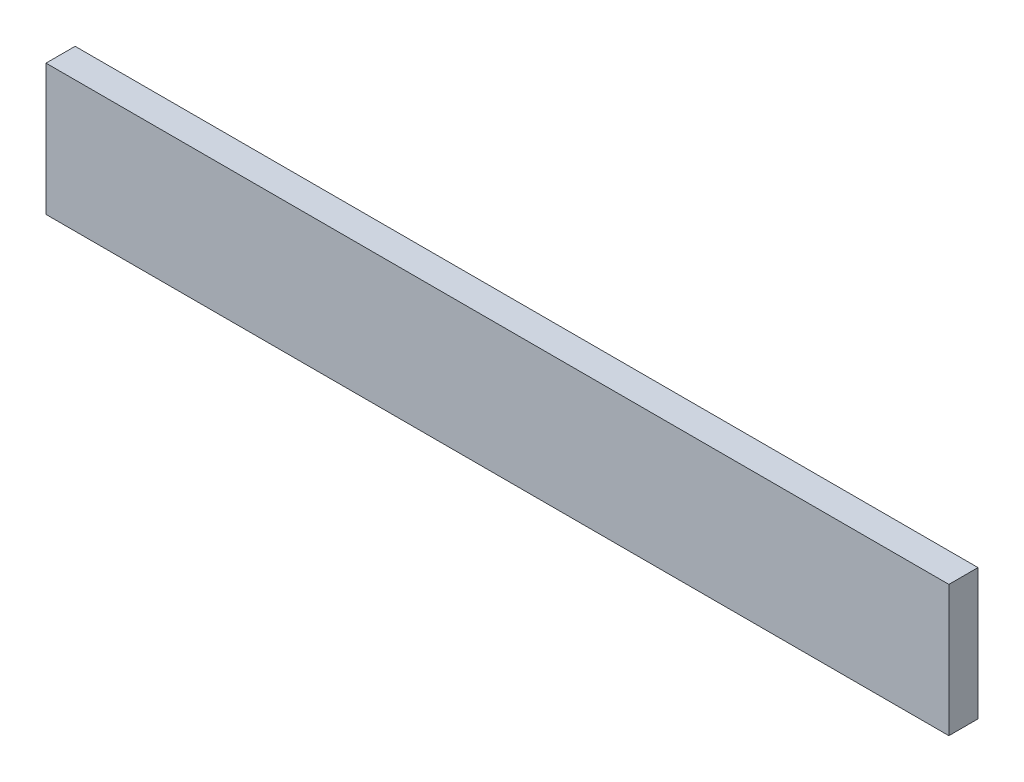
SolidWorks part; units mm, degrees
ref_plane "Alzado" through (0, 0, 0) normal (0, 0, 1) x (1, 0, 0)
ref_plane "Planta" through (0, 0, 0) normal (0, 1, 0) x (1, 0, 0)
ref_plane "Vista lateral" through (0, 0, 0) normal (1, 0, 0) x (0, 0, -1)
sketch "Croquis1" plane through (0, 0, 0) normal (0, 0, 1) x (1, 0, 0)
  line L1 (310, -45) -> (-310, -45)
  line L2 (310, -45) -> (310, 45)
  line L3 (310, 45) -> (-310, 45)
  line L4 (-310, -45) -> (-310, 45)
  line L5 (310, -45) -> (-310, 45) construction
  line L6 (310, 45) -> (-310, -45) construction
  point P0 (0, 0)
  dimension "D1" = 620
  dimension "D2" = 90
extrude "Saliente-Extruir1" add sketch "Croquis1" along normal blind 20
